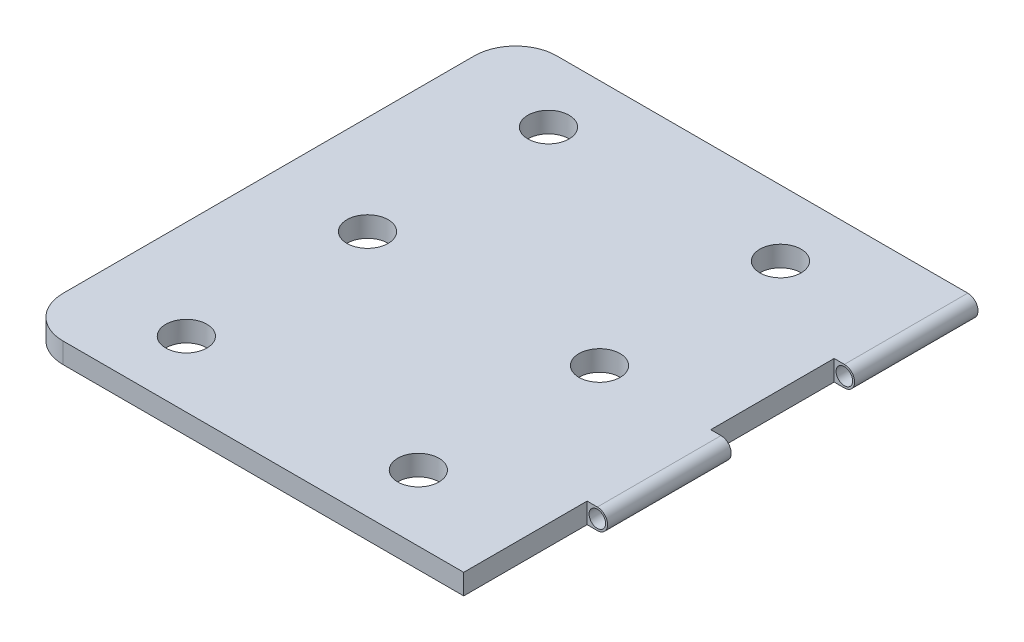
SolidWorks part; units mm, degrees
material "Nylon 101"
ref_plane "Front" through (0, 0, 0) normal (0, 0, 1) x (1, 0, 0)
ref_plane "Top" through (0, 0, 0) normal (0, 1, 0) x (1, 0, 0)
ref_plane "Right" through (0, 0, 0) normal (1, 0, 0) x (0, 0, -1)
sketch "Sketch1" plane through (0, 0, 0) normal (0, 1, 0) x (1, 0, 0)
  line L1 (0, 0) -> (17.84, 0)
  line L2 (0, 0) -> (0, 19.05)
  line L3 (0, 19.05) -> (17.84, 19.05)
  line L4 (17.84, 0) -> (17.84, 19.05)
  dimension "D1" = 17.84
  dimension "D2" = 19.05
extrude "Boss-Extrude1" add sketch "Sketch1" along normal blind 0.79
sketch "Sketch2" plane through (0, 0.79, 0) normal (0, 1, 0) x (1, 0, 0)
  line L0 (17.84, 0) -> (17.84, 19.05) construction
  line L1 (17.84, 14.29) -> (17.05, 14.29)
  line L2 (17.84, 14.29) -> (17.84, 9.53)
  line L3 (17.84, 9.53) -> (17.05, 9.53)
  line L4 (17.05, 14.29) -> (17.05, 9.53)
  line L5 (0, 19.05) -> (0, 0) construction
  line L6 (17.84, 19.05) -> (0, 19.05) construction
  line L7 (0, 0) -> (17.84, 0) construction
  line L8 (17.84, 0) -> (17.05, 0)
  line L9 (17.84, 0) -> (17.84, 4.76)
  line L10 (17.84, 4.76) -> (17.05, 4.76)
  line L11 (17.05, 0) -> (17.05, 4.76)
  circle A0 centre (12.76, 2.54) radius 0.795
  circle A1 centre (3.81, 2.54) radius 0.795
  circle A2 centre (3.81, 9.53) radius 0.795
  circle A3 centre (12.76, 9.53) radius 0.795
  circle A4 centre (12.76, 16.51) radius 0.795
  circle A5 centre (3.81, 16.51) radius 0.795
  dimension "D6" = 1.59
  dimension "D7" = 1.59
  dimension "D8" = 1.59
  dimension "D9" = 1.59
  dimension "D10" = 1.59
  dimension "D11" = 1.59
  dimension "D2" = 4.76
  dimension "D3" = 4.76
  dimension "D4" = 4.76
  dimension "D5" = 4.77
  dimension "D12" = 2.54
  dimension "D13" = 2.54
  dimension "D14" = 3.81
  dimension "D15" = 5.08
  dimension "D16" = 0.79
  dimension "D17" = 0.79
extrude "Cut-Extrude1" cut sketch "Sketch2" against normal blind 2.54
sketch "Sketch4" plane through (0, 0, 0) normal (0, 0, 1) x (1, 0, 0)
  line L0 (17.05, 0) -> (17.84, 0) construction
  line L1 (17.84, 0.79) -> (17.05, 0.79) construction
  line L2 (17.84, 0) -> (17.84, 0.79) construction
  line L3 (17.05, 0) -> (17.84, 0)
  line L4 (17.84, 0.79) -> (17.05, 0.79)
  line L5 (17.84, 0) -> (17.84, 0.79)
  circle A0 centre (17.445, 0.395) radius 0.32
  circle A1 centre (17.445, 0.395) radius 0.395
  dimension "D1" = 0.64
  dimension "D2" = 0.79
extrude "Cut-Extrude2" cut sketch "Sketch4" against normal through all contours A0 | A1 L5 L4 | A1 L3 L5
fillet "Fillet1" radius 1.59 2 edges at (0, 0.395, -19.05) (0, 0.395, 0)
